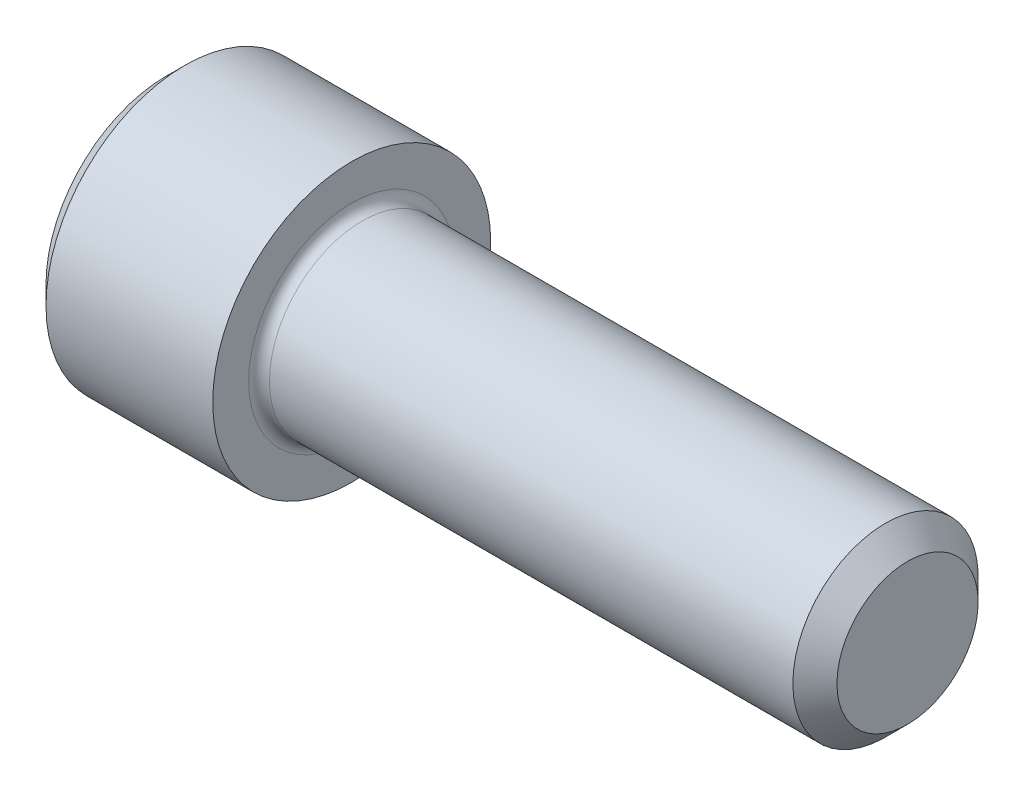
SolidWorks part; units mm, degrees
ref_plane "Plane1" through (0, 0, 0) normal (0, 0, 1) x (1, 0, 0)
ref_plane "Plane2" through (0, 0, 0) normal (0, 1, 0) x (1, 0, 0)
ref_plane "Plane3" through (0, 0, 0) normal (1, 0, 0) x (0, 0, -1)
sketch "BodySke" plane through (0, 0, 0) normal (0, 0, 1) x (1, 0, 0)
  line L0 (0, 0) -> (0, 4.1275)
  line L1 (0.635, 4.7625) -> (6.35, 4.7625)
  line L2 (6.35, 4.7625) -> (6.35, 3.175)
  line L3 (6.35, 3.175) -> (24.6444, 3.175)
  line L4 (25.4, 2.4193) -> (25.4, 0)
  line L5 (25.4, 0) -> (0, 0)
  line L6 (-31.75, 0) -> (127, 0) construction
  line L7 (0, 4.1275) -> (0.635, 4.7625)
  line L8 (25.4, 2.4193) -> (24.6444, 3.175)
  line L9 (0, -4.1275) -> (0.635, -4.7625) construction
  line L10 (25.4, -2.4193) -> (24.6444, -3.175) construction
  line L11 (7.62, 9.525) -> (7.62, 3.175) construction
  line L12 (6.35, 9.525) -> (6.35, 3.175) construction
  line L13 (-12.7, 9.525) -> (-12.7, 3.175) construction
  dimension "Diameter" = 6.35
  dimension "Head_ht" = 6.35
  dimension "Length" = 19.05
  dimension "Body_ch_ang" = 45
  dimension "Head_dia" = 9.525
  dimension "Head_ch_ang" = 45
  dimension "Head_side_ht" = 5.715
  dimension "Minor_dia" = 4.8387
  dimension "Advance" = 1.27
  dimension "Thread_nom" = 19.05
  dimension "Thread_length" = 38.1
revolve "Base-Revolve" add sketch "BodySke"
cosmetic thread "ThreadCosmetic" [suppressed]
fillet "Fillet1" radius 0.3556 1 edges at (6.35, 0, 3.175)
sketch "Sketch2" plane through (0, 0, 0) normal (0, 0, 1) x (1, 0, 0)
  line L0 (0, 2.3813) -> (3.048, 2.3813)
  line L1 (3.048, 2.3813) -> (4.4228, 0)
  line L2 (-31.75, 0) -> (127, 0) construction
  line L3 (4.4228, 0) -> (0, 0)
  line L4 (0, 0) -> (0, 2.3813)
  line L5 (0, 4.1275) -> (0, -4.1275) construction
  line L6 (0, 0) -> (47.625, 0) construction
  line L7 (6.35, -4.7625) -> (6.35, 4.7625) construction
  dimension "D1" = 2.3813
  dimension "D2" = 60
  dimension "Wall_thickness" = 3.302
revolve "Hex-PreBroach" cut sketch "Sketch2" angle 360 about L6
sketch "Sketch3" plane through (0, 0, 0) normal (-1, 0, 0) x (0, 0.5, 0.866)
  line L0 (1.3748, 2.3813) -> (-1.3748, 2.3813)
  line L1 (-1.3748, 2.3813) -> (-2.7496, 0)
  line L2 (1.3748, 2.3813) -> (2.7496, 0)
  line L3 (1.3748, -2.3812) -> (2.7496, 0)
  line L4 (1.3748, -2.3812) -> (-1.3748, -2.3812)
  line L5 (-1.3748, -2.3812) -> (-2.7496, 0)
  dimension "D1" = 2.3813
  dimension "D2" = 2.3813
  dimension "Hex_size" = 4.7625
extrude "Hex" cut sketch "Sketch3" against normal blind 3.048
sketch "Sketch4" plane through (0, 0, 0) normal (-1, 0, 0) x (0, 0, 1)
  line L0 (0, 0) -> (2.8067, 0)
  line L1 (0, 0) -> (6.1484, 3.5498) construction
  line L2 (0, 0) -> (1.4033, 2.4307)
  line L3 (2.3336, 0.614) -> (2.6851, 0.817)
  line L4 (1.6986, 1.7139) -> (2.0501, 1.9169)
  arc A0 (2.3336, 0.614) -> (1.6986, 1.7139) centre (0, 0) ccw
  arc A1 (2.8067, 0) -> (2.6851, 0.817) centre (0, 0) ccw
  arc A2 (1.4033, 2.4307) -> (2.0501, 1.9169) centre (0, 0) cw
  dimension "D1" = 30
  dimension "Spline_n_dim" = 4.826
  dimension "Spline_m_dim" = 5.6134
  dimension "D2" = 60
  dimension "D3" = 0.635
  dimension "Spline_p_dim" = 1.27
extrude "Spline" [suppressed] cut sketch "Sketch4" against normal blind 3.048
pattern_circular "CirPattern1" [suppressed] count 6 every 60
sketch "Sketch5" plane through (0, 0, 0) normal (0, 0, 1) x (1, 0, 0)
  line L0 (-31.75, 0) -> (127, 0) construction
  line L2 (0, 4.1275) -> (0, -4.1275) construction
  circle A0 centre (2.159, 0) radius 0.5905
  dimension "Drilled_hole_dia" = 1.1811
  dimension "Drilled_hole_loc" = 2.159
extrude "Hole" [suppressed] cut sketch "Sketch5" against normal through all and the other way through all
pattern_circular "Drilled-4" [suppressed] count 2 every 60
pattern_circular "Drilled-6" [suppressed] count 3 every 60
sketch "ThdSchSke" plane through (0, 0, 0) normal (0, 0, 1) x (1, 0, 0)
  line L0 (7.62, -2.4193) -> (7.0909, -3.175)
  line L1 (7.62, -2.4193) -> (8.1491, -3.175)
  line L2 (8.1491, -3.175) -> (8.1491, -3.9688)
  line L3 (-3.175, 0) -> (5.1513, 0) construction
  line L5 (8.1491, -3.9688) -> (7.0909, -3.9688)
  line L6 (7.0909, -3.9688) -> (7.0909, -3.175)
  line L7 (0, 4.1275) -> (0, -4.1275) construction
  dimension "Thread_minor" = 4.8387
  dimension "Diameter" = 6.35
  dimension "Start" = 7.62
  dimension "SideAngle" = 55
  dimension "VeeAngle" = 70
  dimension "Overcut" = 7.9375
revolve "ThreadSchematic" [suppressed] cut sketch "ThdSchSke" angle 360 about L3
pattern_linear "ThdSchPat" [suppressed]
equation "\"D2@Sketch3\" = \"Hex_size@Sketch3\" / 2"
equation "\"D1@Sketch3\" = \"Hex_size@Sketch3\" / 2"
equation "\"D1@Sketch2\" = \"Hex_size@Sketch3\" / 2"
equation "\"D3@Sketch4\" = \"Spline_p_dim@Sketch4\" / 2"
equation "\"Thread_minor@ThreadCosmetic\"  =  \"Minor_dia@BodySke\""
equation "\"D2@CirPattern1\" = 360 / \"Num_teeth@CirPattern1\""
equation "\"Wall_thickness@Sketch2\" = \"Head_ht@BodySke\" - \"Key_eng@Hex\""
equation "\"Thread_length@ThreadCosmetic\" = ((sgn( (\"Length@BodySke\" - \"Advance@BodySke\" ) - \"Thread_nom@BodySke\" )-1)*( (\"Length@BodySke\" - \"Advance@BodySke\" ) - \"Thread_nom@BodySke\" ))/-2+ \"Thread_nom@BodySke\""
equation "\"Thread_minor@ThdSchSke\" = \"Minor_dia@BodySke\""
equation "\"Diameter@ThdSchSke\" = \"Diameter@BodySke\""
equation "\"Overcut@ThdSchSke\" = \"Diameter@BodySke\" * 1.25"
equation "\"Start@ThdSchSke\" = \"Head_ht@BodySke\" + \"Length@BodySke\" - \"Thread_length@ThreadCosmetic\"  '---Non-countersunk---"
equation "\"Num_threads@ThdSchPat\" = int( \"Thread_length@ThreadCosmetic\" / \"Advance@BodySke\" + 0.999 )  + 1"
equation "\"Advance@ThdSchPat\" = \"Thread_length@ThreadCosmetic\" /  (\"Num_threads@ThdSchPat\" - 1) 'relax it"
equation "\"Num_threads@ThdSchPat\" = \"Num_threads@ThdSchPat\" - sgn( \"Num_threads@ThdSchPat\" - 1) '---chamfered tips only---"
